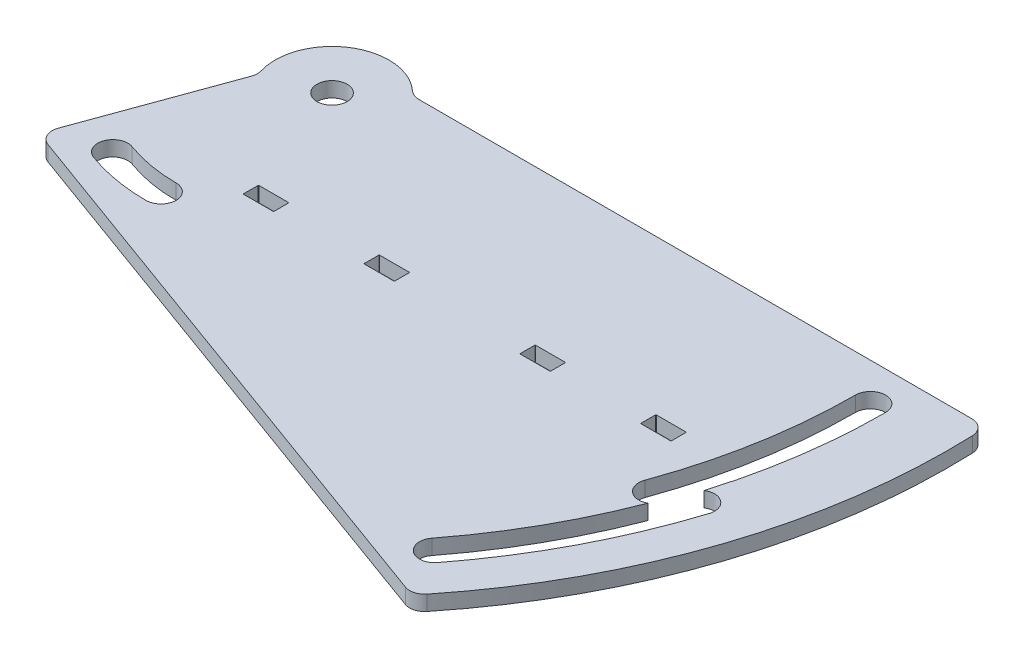
SolidWorks part; units mm, degrees
ref_plane "Front Plane" through (0, 0, 0) normal (0, 0, 1) x (1, 0, 0)
ref_plane "Top Plane" through (0, 0, 0) normal (0, 1, 0) x (1, 0, 0)
ref_plane "Right Plane" through (0, 0, 0) normal (1, 0, 0) x (0, 0, -1)
sketch "Sketch1" plane through (0, 0, 0) normal (0, 1, 0) x (1, 0, 0)
  line L0 (0, 24.5) -> (0, -24.5) construction
  line L1 (-62, 24.5) -> (62, 24.5)
  line L2 (-62, 24.5) -> (-62, -24.5)
  line L3 (-62, -24.5) -> (62, -24.5)
  line L4 (62, 24.5) -> (62, -24.5)
  line L5 (-62, 24.5) -> (62, -24.5) construction
  line L6 (-62, -24.5) -> (62, 24.5) construction
  line L7 (-62, 0) -> (62, 0) construction
  line L8 (-62, 0) -> (54.5219, -42.4105) construction
  line L9 (-58.9231, 26.9497) -> (57.5987, -15.4608)
  line L10 (-58.9231, 26.9497) -> (-75.6821, -19.0952)
  line L11 (57.5987, -15.4608) -> (40.8398, -61.5057)
  line L12 (-75.6821, -19.0952) -> (40.8398, -61.5057)
  line L13 (-58.9231, 26.9497) -> (40.8398, -61.5057) construction
  line L14 (57.5987, -15.4608) -> (-75.6821, -19.0952) construction
  line L15 (-0.6622, 5.7445) -> (-17.4212, -40.3005) construction
  line L16 (-67.3026, 3.9273) -> (49.2193, -38.4832) construction
  line L17 (53.515, 17) -> (53.515, -17) construction
  line L18 (-53.515, 17) -> (53.515, 17) construction
  line L19 (47.0603, -19.6064) -> (35.4316, -51.556) construction
  line L20 (-53.515, 17) -> (47.0603, -19.6064) construction
  line L21 (62, 24.5) -> (68.9991, 24.5)
  circle A0 centre (53.515, 17) radius 3
  circle A1 centre (-53.515, 17) radius 3
  circle A2 centre (53.515, -17) radius 3
  circle A3 centre (-53.515, -17) radius 3
  circle A4 centre (47.0603, -19.6064) radius 3
  circle A5 centre (35.4316, -51.556) radius 3
  circle A6 centre (-65.1437, -14.9495) radius 3
  circle A7 centre (-53.515, 17) radius 3
  circle A8 centre (-53.515, 17) radius 37
  circle A9 centre (-53.515, 17) radius 31
  circle A10 centre (-53.515, 17) radius 104.03
  circle A11 centre (-53.515, 17) radius 110.03
  circle A12 centre (-53.515, 17) radius 109.3006
  circle A13 centre (-53.515, 17) radius 115.3006
  circle A14 centre (-53.515, 17) radius 122.7435
  circle A15 centre (-53.515, 17) radius 11.3245
  point P0 (0, 0)
  point P20 (-9.0417, -17.278)
  dimension "D5" = 6
  dimension "D1" = 49
  dimension "D2" = 124
  dimension "D3" = 34
  dimension "D4" = 107.03
  dimension "D6" = 20
extrude "Boss-Extrude1" add sketch "Sketch1" along normal blind 3 contours L2 A15 L9 L1 L10 A1 | L10 L1 L2 | L10 A15 L1 | L9 L10 L1 | L9 A15 L1 | A15 L9 A9 L1 | A15 L2 A9 L9 | A15 L10 A9 L2 | L10 A15 L2 | L2 A15 L10 | L1 A15 L9 | A9 L10 A8 A6 | A8 L10 L12 L2 | A9 A3 A8 L9 | L12 A10 L3 | A9 L9 A8 L1 | A0 A12 L1 A10 | L9 A13 L1 A11 A2 | L4 A14 L21 | A12 A0 A11 L1 | L11 A14 L3 | A13 L12 L11 L3 | L3 A10 L9 A8 L2 L12 | L12 A13 A5 A11 | A12 L12 A11 A5 | L12 A12 L3 A10 | L3 A12 A4 A10 | A11 A2 L9 | A2 A13 L9 | A13 L3 L11 L9 | A13 L9 L11 L3 L4 L1 | L9 A10 L1 A8
fillet "Fillet1" radius 3 5 edges at (-45.03, 1.5, -24.5) (-64.0534, 1.5, -12.8543) (68.9991, 1.5, -24.5) (40.8398, 1.5, 61.5057) (-75.6821, 1.5, 19.0952)
sketch "weld sketch" plane through (0, 3, 0) normal (0, 1, 0) x (1, 0, 0)
  line L0 (-64.4163, 11.8575) -> (-74.6561, -16.2761) construction
  line L1 (-2.4152, 24.5) -> (-2.4152, -45.7622) construction
  line L2 (-43.7712, 24.5) -> (66.1439, 24.5) construction
  line L3 (-71.5431, -7.7234) -> (66.7128, -7.7234) construction
  line L4 (-14.9152, -20.2234) -> (10.0848, -20.2234)
  line L5 (-14.9152, -20.2234) -> (-14.9152, 4.7766)
  line L6 (10.0848, -20.2234) -> (10.0848, 4.7766)
  line L7 (-14.9152, 4.7766) -> (10.0848, 4.7766)
  line L8 (-14.9152, -20.2234) -> (10.0848, 4.7766) construction
  line L9 (10.0848, -20.2234) -> (-14.9152, 4.7766) construction
  line L10 (-14.9152, 4.7766) -> (-14.9152, 24.5) construction
  line L11 (-14.9152, -20.2234) -> (-21.661, -38.7573) construction
  line L12 (-72.863, -20.1213) -> (38.8386, -60.7773) construction
  line L13 (40.0848, -6.2234) -> (10.0848, -6.2234)
  line L14 (-44.9152, -6.2234) -> (-14.9152, -6.2234)
  line L15 (-44.9152, -6.2234) -> (-44.9152, -9.2234)
  line L16 (-44.9152, -9.2234) -> (-14.9152, -9.2234)
  line L17 (-14.9152, -6.2234) -> (-14.9152, -9.2234)
  line L18 (-44.9152, -6.2234) -> (-14.9152, -9.2234) construction
  line L19 (-44.9152, -9.2234) -> (-14.9152, -6.2234) construction
  line L20 (40.0848, -6.2234) -> (40.0848, -9.2234)
  line L21 (40.0848, -9.2234) -> (10.0848, -9.2234)
  line L22 (-38.9152, -6.2234) -> (-38.9152, -9.2234)
  line L23 (-29.9152, -6.2234) -> (-29.9152, -9.2234) construction
  line L24 (-20.9152, -6.2234) -> (-20.9152, -9.2234)
  line L25 (-44.9152, -6.2234) -> (-38.9152, -9.2234) construction
  line L26 (-44.9152, -6.2234) -> (-44.9402, -6.2234) construction
  line L27 (-44.9402, -9.2484) -> (-38.8902, -9.2484)
  line L28 (-44.9402, -9.2484) -> (-44.9402, -6.1984)
  line L29 (-44.9402, -6.1984) -> (-38.8902, -6.1984)
  line L30 (-38.8902, -9.2484) -> (-38.8902, -6.1984)
  line L31 (-44.9402, -9.2484) -> (-38.8902, -6.1984) construction
  line L32 (-44.9402, -6.1984) -> (-38.8902, -9.2484) construction
  line L33 (-44.9152, -6.2234) -> (-44.9152, -6.1984) construction
  line L34 (-20.9152, -6.2234) -> (-14.9152, -9.2234) construction
  line L35 (-20.9152, -6.2234) -> (-20.9152, -6.1984) construction
  line L36 (-14.8902, -9.2484) -> (-20.9402, -9.2484)
  line L37 (-14.8902, -9.2484) -> (-14.8902, -6.1984)
  line L38 (-14.8902, -6.1984) -> (-20.9402, -6.1984)
  line L39 (-20.9402, -9.2484) -> (-20.9402, -6.1984)
  line L40 (-14.8902, -9.2484) -> (-20.9402, -6.1984) construction
  line L41 (-14.8902, -6.1984) -> (-20.9402, -9.2484) construction
  line L42 (-14.9152, -6.2234) -> (-14.8902, -6.2234) construction
  line L43 (40.1098, -9.2484) -> (40.1098, -6.1984)
  line L44 (40.1098, -6.1984) -> (34.0598, -6.1984)
  line L45 (34.0598, -9.2484) -> (34.0598, -6.1984)
  line L46 (40.1098, -9.2484) -> (34.0598, -9.2484)
  line L47 (10.0598, -9.2484) -> (10.0598, -6.1984)
  line L48 (10.0598, -6.1984) -> (16.1098, -6.1984)
  line L49 (16.1098, -9.2484) -> (16.1098, -6.1984)
  line L50 (10.0598, -9.2484) -> (16.1098, -9.2484)
  arc A3 (42.2042, -59.8362) -> (69.1418, 21.6127) centre (-53.515, 17) ccw construction
  point P13 (-29.9152, -7.7234)
  point P18 (-2.4152, -7.7234)
  point P35 (-41.9152, -7.7234)
  point P40 (-17.9152, -7.7234)
  point P47 (-20.9873, -6.1513)
  dimension "D1" = 25
  dimension "D2" = 3
  dimension "D3" = 30
  dimension "D4" = 6
  dimension "D5" = 0.025
extrude "Cut-Extrude1" cut sketch "weld sketch" against normal up to next contours L28 L29 L30 L27 | L39 L38 L37 L36 | L50 L49 L48 L47 | L46 L45 L44 L43
fillet "Fillet2" radius 0.1 16 edges at (-38.8902, 1.5, 9.2484) (-14.8902, 1.5, 9.2484) (16.1098, 1.5, 9.2484) (40.1098, 1.5, 9.2484) (34.0598, 1.5, 9.2484) (10.0598, 1.5, 9.2484) (-20.9402, 1.5, 9.2484) (-44.9402, 1.5, 9.2484) (-38.8902, 1.5, 6.1984) (-14.8902, 1.5, 6.1984) (16.1098, 1.5, 6.1984) (40.1098, 1.5, 6.1984) (34.0598, 1.5, 6.1984) (10.0598, 1.5, 6.1984) (-20.9402, 1.5, 6.1984) (-44.9402, 1.5, 6.1984)
equation "\"TOLERANCE\"= 0.025"
equation "\"D5@weld sketch\"=\"TOLERANCE\""
